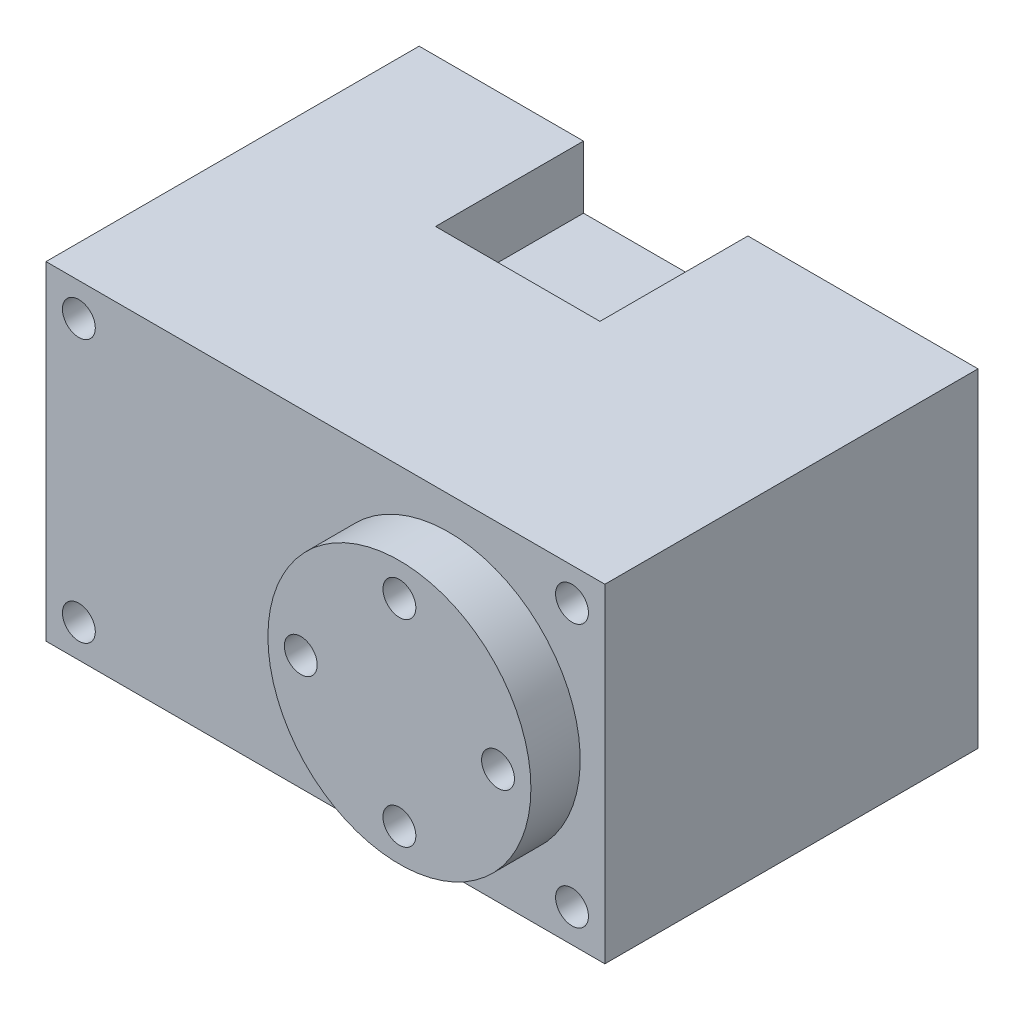
SolidWorks part; units mm, degrees
ref_plane "前视基准面" through (0, 0, 0) normal (0, 0, 1) x (1, 0, 0)
ref_plane "上视基准面" through (0, 0, 0) normal (0, 1, 0) x (1, 0, 0)
ref_plane "右视基准面" through (0, 0, 0) normal (1, 0, 0) x (0, 0, -1)
sketch "草图1" plane through (0, 0, 0) normal (0, 0, 1) x (1, 0, 0)
  line L1 (-17, -10) -> (17, -10)
  line L2 (-17, -10) -> (-17, 10)
  line L3 (-17, 10) -> (17, 10)
  line L4 (17, -10) -> (17, 10)
  line L5 (-17, -10) -> (17, 10) construction
  line L6 (-17, 10) -> (17, -10) construction
  point P0 (0, 0)
  dimension "D1" = 34
  dimension "D2" = 20
extrude "凸台-拉伸1" add sketch "草图1" along normal blind 22.7
sketch "草图2" plane through (0, 0, 22.7) normal (0, 0, 1) x (1, 0, 0)
  circle A0 centre (7.5, 0) radius 8
  dimension "D1" = 16
  dimension "D2" = 7.5
extrude "凸台-拉伸2" add sketch "草图2" along normal blind 3
sketch "草图3" plane through (0, 0, 22.7) normal (0, 0, 1) x (1, 0, 0)
  line L0 (0, 0) -> (0, 12.6804) construction
  line L1 (0, 0) -> (12.2778, 0) construction
  circle A0 centre (-15, 8) radius 1
  circle A1 centre (15, 8) radius 1
  circle A2 centre (-15, -8) radius 1
  circle A3 centre (15, -8) radius 1
  dimension "D1" = 30
  dimension "D2" = 16
  dimension "D3" = 2
extrude "切除-拉伸1" cut sketch "草图3" against normal blind 6
sketch "草图5" plane through (0, 0, 0) normal (0, 0, -1) x (-1, 0, 0)
  line L0 (0, 7.5921) -> (0, -5.5629) construction
  line L1 (-4.8281, 0) -> (7.907, 0) construction
  circle A0 centre (-15, 8) radius 1
  circle A1 centre (15, 8) radius 1
  circle A2 centre (-15, -8) radius 1
  circle A3 centre (15, -8) radius 1
  dimension "D1" = 2
  dimension "D2" = 16
  dimension "D3" = 30
extrude "切除-拉伸2" cut sketch "草图5" against normal blind 6
sketch "草图6" plane through (0, 0, 0) normal (0, 0, -1) x (-1, 0, 0)
  line L0 (0, 0) -> (-15.569, 0) construction
  circle A0 centre (-7.5, 0) radius 5
  dimension "D2" = 10
  dimension "D1" = 7.5
extrude "切除-拉伸3" cut sketch "草图6" against normal blind 1
sketch "草图7" plane through (0, 0, 1) normal (0, 0, -1) x (-1, 0, 0)
  circle A0 centre (-7.5, 0) radius 2.5
  dimension "D1" = 5
extrude "切除-拉伸4" cut sketch "草图7" against normal blind 2
sketch "草图8" plane through (0, 10, 0) normal (0, 1, 0) x (1, 0, 0)
  line L0 (17, 0) -> (-17, 0) construction
  line L1 (-7, 0) -> (3, 0)
  line L2 (-7, 0) -> (-7, -9)
  line L3 (-7, -9) -> (3, -9)
  line L4 (3, 0) -> (3, -9)
  line L5 (-17, -22.7) -> (-17, 0) construction
  dimension "D1" = 10
  dimension "D2" = 10
  dimension "D3" = 9
extrude "切除-拉伸5" cut sketch "草图8" against normal blind 3.8
mirror "镜向1" about plane through (0, 0, 0) normal (0, 1, 0) of "切除-拉伸5"
sketch "草图9" plane through (0, 0, 3) normal (0, 0, -1) x (-1, 0, 0)
  circle A0 centre (-7.5, 0) radius 1.25
  dimension "D1" = 2.5
extrude "切除-拉伸6" cut sketch "草图9" against normal blind 3.8
sketch "草图10" plane through (0, 0, 25.7) normal (0, 0, 1) x (1, 0, 0)
  circle A0 centre (13.5, 0) radius 1
  circle A1 centre (7.5, 0) radius 8 construction
  dimension "D2" = 2
  dimension "D1" = 6
extrude "切除-拉伸7" cut sketch "草图10" against normal blind 6
pattern_circular "阵列(圆周)1" count 4 every 90 about axis through (7.5, 0, 0) along (0, 0, 1) of "切除-拉伸7"
